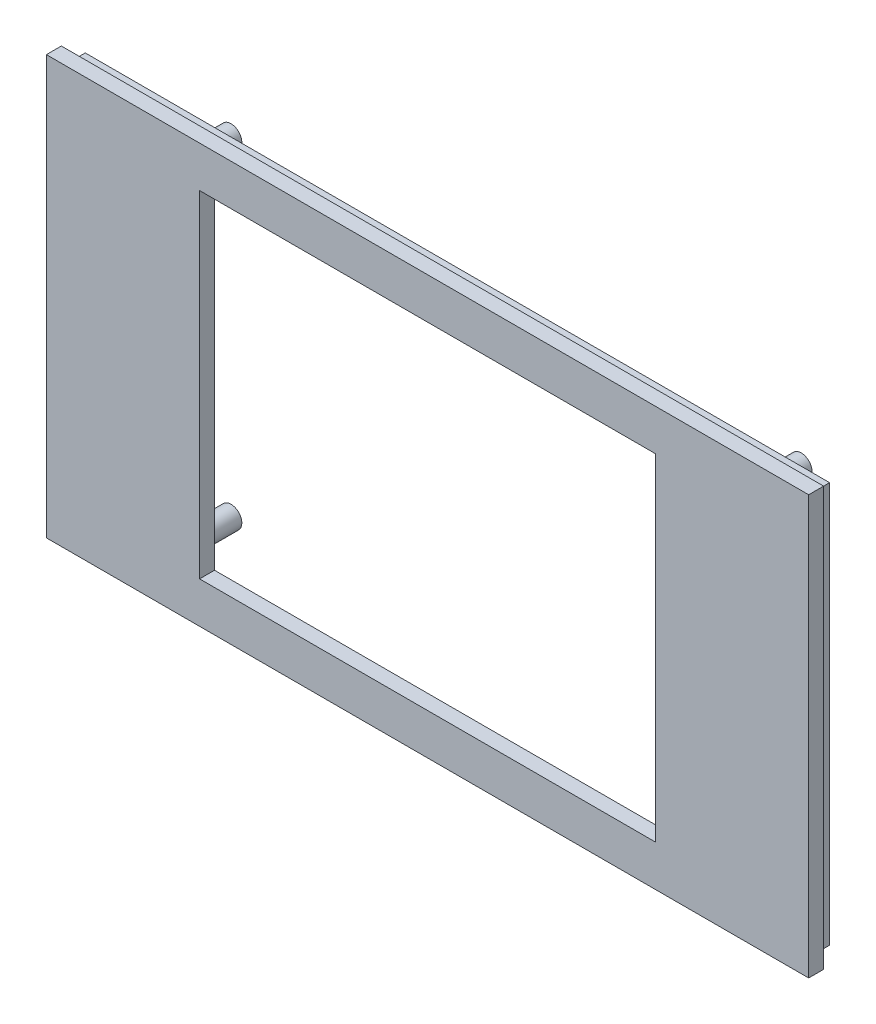
SolidWorks part; units mm, degrees
material "ABS"
ref_plane "Front Plane" through (0, 0, 0) normal (0, 0, 1) x (1, 0, 0)
ref_plane "Top Plane" through (0, 0, 0) normal (0, 1, 0) x (1, 0, 0)
ref_plane "Right Plane" through (0, 0, 0) normal (1, 0, 0) x (0, 0, -1)
sketch "Sketch1" plane through (0, 0, 0) normal (0, 0, 1) x (1, 0, 0)
  line L1 (-51, -28) -> (51, -28)
  line L2 (-51, -28) -> (-51, 28)
  line L3 (-51, 28) -> (51, 28)
  line L4 (51, -28) -> (51, 28)
  line L5 (-51, -28) -> (51, 28) construction
  line L6 (-51, 28) -> (51, -28) construction
  line L7 (-30.5, -22.5) -> (30.5, -22.5)
  line L8 (-30.5, -22.5) -> (-30.5, 22.5)
  line L9 (-30.5, 22.5) -> (30.5, 22.5)
  line L10 (30.5, -22.5) -> (30.5, 22.5)
  line L11 (-30.5, -22.5) -> (30.5, 22.5) construction
  line L12 (-30.5, 22.5) -> (30.5, -22.5) construction
  point P0 (0, 0)
  point P6 (0, 0)
  point P11 (-2.0435, -14.1498)
  point P12 (0, 0)
  dimension "D1" = 56
  dimension "D2" = 102
  dimension "D3" = 45
  dimension "D4" = 61
extrude "Front" add sketch "Sketch1" along normal blind 2
sketch "Sketch2" plane through (0, 0, 0) normal (0, 0, -1) x (-1, 0, 0)
  line L0 (-51, 28) -> (51, 28) construction
  line L1 (-51, -28) -> (-51, 28) construction
  line L2 (51, -28) -> (-51, -28) construction
  line L3 (51, 28) -> (51, -28) construction
  line L5 (-49.8, 26.8) -> (49.8, 26.8)
  line L6 (-49.8, 26.8) -> (-49.8, -26.8)
  line L7 (-49.8, -26.8) -> (49.8, -26.8)
  line L8 (49.8, 26.8) -> (49.8, -26.8)
  line L9 (48.6, 25.6) -> (-48.6, 25.6)
  line L10 (48.6, 25.6) -> (48.6, -25.6)
  line L11 (48.6, -25.6) -> (-48.6, -25.6)
  line L12 (-48.6, 25.6) -> (-48.6, -25.6)
  dimension "D1" = 1.2
  dimension "D2" = 1.2
  dimension "D3" = 1.2
  dimension "D4" = 1.2
  dimension "D5" = 1.2
  dimension "D6" = 1.2
  dimension "D7" = 1.2
  dimension "D8" = 1.2
extrude "WALLS" add sketch "Sketch2" along normal blind 2
sketch "Sketch3" plane through (0, 0, 0) normal (0, 0, -1) x (-1, 0, 0)
  line L0 (-30.5, -22.5) -> (-30.5, 22.5) construction
  line L1 (49.8, 26.8) -> (-49.8, 26.8) construction
  line L3 (30.5, 22.5) -> (30.5, -22.5) construction
  line L4 (-49.8, -26.8) -> (49.8, -26.8) construction
  line L6 (49.8, 26.8) -> (-49.8, 26.8) construction
  circle A0 centre (-41, 21.9) radius 1.45
  circle A1 centre (35.3, 21.9) radius 1.45
  circle A2 centre (-41, -22.2) radius 1.45
  circle A3 centre (35.3, -22.2) radius 1.45
  dimension "D1" = 10.5
  dimension "D2" = 4.9
  dimension "D3" = 2.9
  dimension "D4" = 4.9
  dimension "D5" = 4.8
  dimension "D6" = 4.6
extrude "SCREW_SPOTS" add sketch "Sketch3" along normal blind 7
